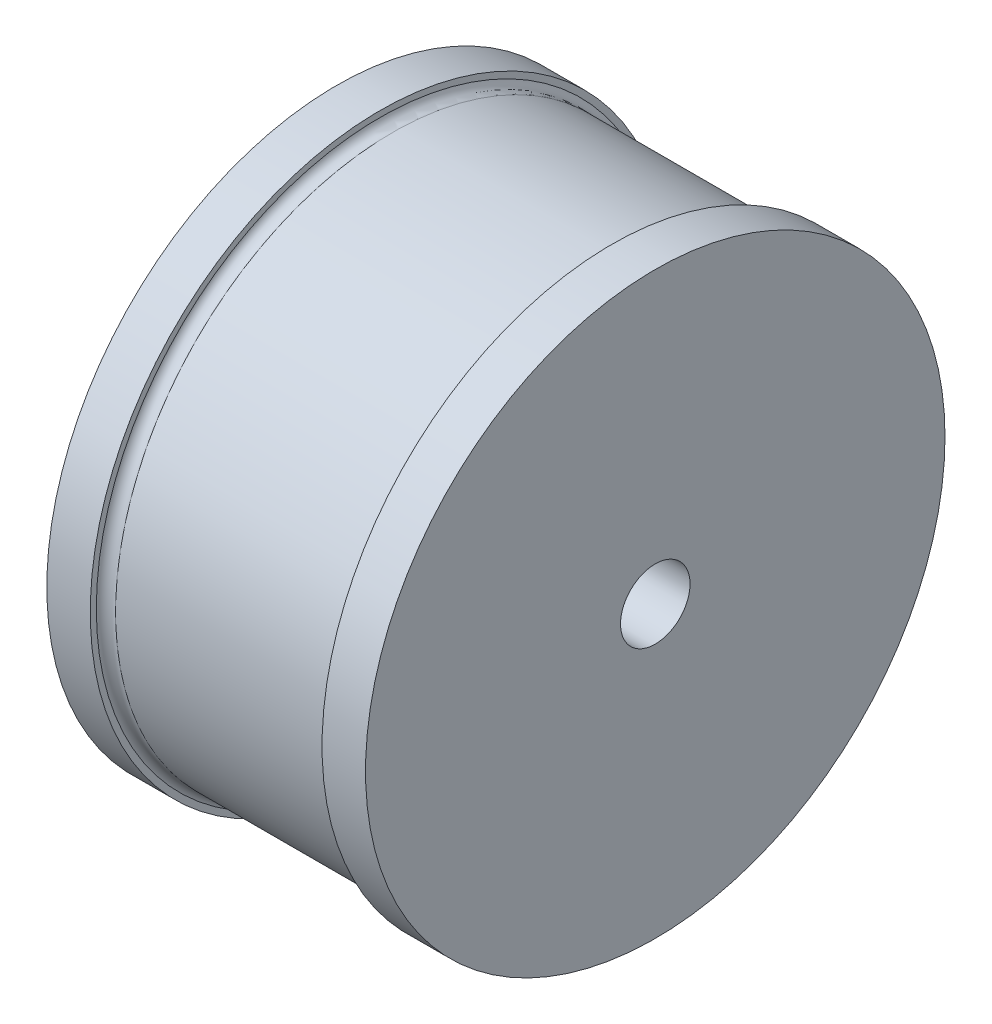
SolidWorks part; units mm, degrees
material "Custom Plastic"
ref_plane "Front Plane" through (0, 0, 0) normal (0, 0, 1) x (1, 0, 0)
ref_plane "Top Plane" through (0, 0, 0) normal (0, 1, 0) x (1, 0, 0)
ref_plane "Right Plane" through (0, 0, 0) normal (1, 0, 0) x (0, 0, -1)
sketch "Sketch1" plane through (0, 0, 0) normal (0, 0, 1) x (1, 0, 0)
  line L0 (23.8765, 28.5009) -> (23.8765, -21.4991)
  line L1 (23.8765, -21.4991) -> (19.3834, -21.4991)
  line L4 (23.8765, 28.5009) -> (16.3765, 28.5009)
  line L5 (16.3765, 28.5009) -> (16.3765, 27.4564)
  line L6 (14.8144, 26.3009) -> (-3.6235, 26.3009)
  line L7 (-31.1235, 20.2266) -> (-31.1235, 28.5009)
  line L8 (-31.1235, 28.5009) -> (-23.6235, 28.5009)
  line L9 (-23.6235, 28.5009) -> (-23.6235, 27.4574)
  line L10 (-21.4619, 26.3009) -> (-3.6235, 26.3009)
  line L13 (-3.6235, 20.2266) -> (-3.6235, 37.3079) construction
  line L17 (-23.6235, -21.4991) -> (-31.1235, -21.4991)
  line L18 (-31.1235, -21.4991) -> (-31.1235, 20.2266)
  line L19 (-23.6235, -21.4991) -> (19.3834, -21.4991)
  arc A2 (-23.6235, 27.4574) -> (-21.4619, 26.3009) centre (-21.9644, 27.96) ccw
  arc A3 (16.3765, 27.4564) -> (14.8144, 26.3009) centre (14.7658, 28.0002) cw
  point P11 (0, 22.5)
  point P18 (9.5, 26.3)
  point P28 (-9.5, 26.3)
  dimension "D3" = 47.8
  dimension "D1" = 50
  dimension "D2" = 7.5
  dimension "D4" = 2.2
  dimension "D5" = 2.1616
revolve "Revolve1" add sketch "Sketch1" angle 360 about L1
sketch "Sketch3" plane through (23.8765, 0, 0) normal (1, 0, 0) x (0, 0, -1)
  circle A0 centre (0, -21.4991) radius 6
extrude "Cut-Extrude1" cut sketch "Sketch3" against normal through all
